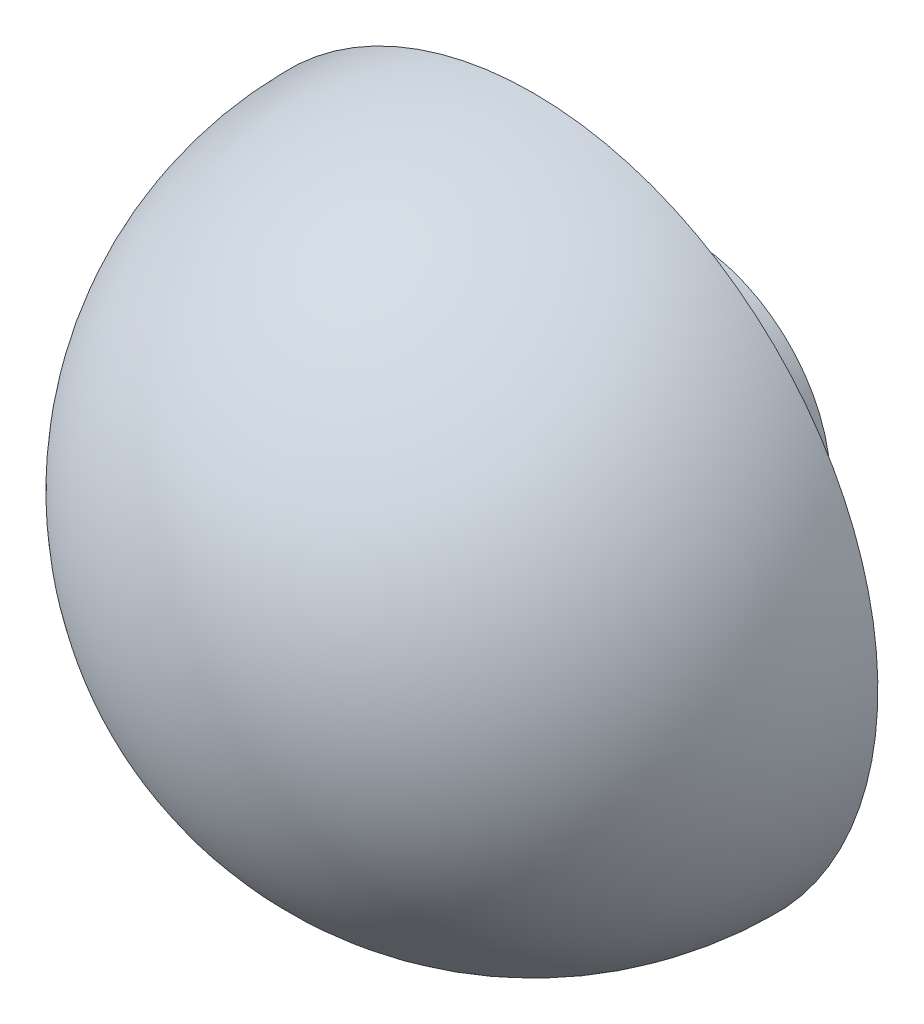
SolidWorks part; units mm, degrees
ref_plane "Alzado" through (0, 0, 0) normal (0, 0, 1) x (1, 0, 0)
ref_plane "Planta" through (0, 0, 0) normal (0, 1, 0) x (1, 0, 0)
ref_plane "Vista lateral" through (0, 0, 0) normal (1, 0, 0) x (0, 0, -1)
sketch "Croquis2" plane through (0, 0, 0) normal (1, 0, 0) x (0, 0, -1)
  line L0 (30, 0) -> (-13.0315, 0) construction
  line L1 (30, 4) -> (30, -4) construction
  line L2 (0, 4) -> (0, 1.65)
  line L3 (0, 1.65) -> (1.8, 1.65)
  line L4 (1.8, 1.65) -> (1.8, 0)
  line L5 (1.8, 0) -> (-4, 0)
  arc A0 (-4, 0) -> (0, 4) centre (0, 0) cw
  point P8 (1.8, 1.65)
  dimension "D2" = 1.8
revolve "Revolución1" add sketch "Croquis2" angle 360 about L0
